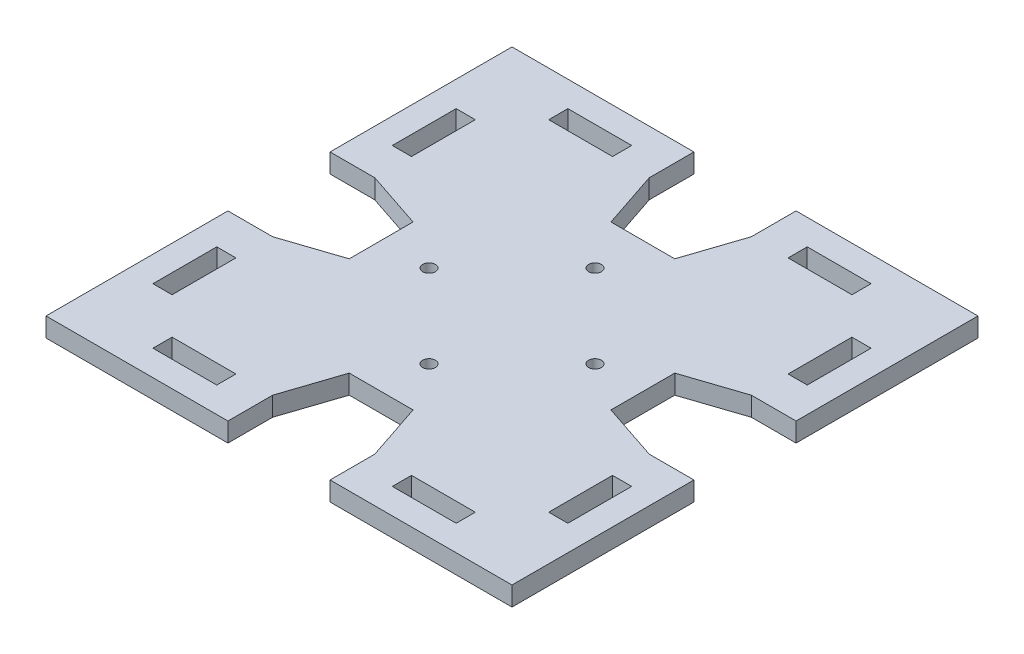
SolidWorks part; units mm, degrees
ref_plane "Front Plane" through (0, 0, 0) normal (0, 0, 1) x (1, 0, 0)
ref_plane "Top Plane" through (0, 0, 0) normal (0, 1, 0) x (1, 0, 0)
ref_plane "Right Plane" through (0, 0, 0) normal (1, 0, 0) x (0, 0, -1)
sketch "Sketch1" plane through (0, 0, 0) normal (0, 1, 0) x (1, 0, 0)
  line L5 (-31.5, 9) -> (-41.5, 9)
  line L6 (-41.5, 9) -> (-44.5, 0)
  line L7 (-31.5, 9) -> (-28.5, 0)
  line L8 (-57, 29.5) -> (-50.5, 29.5)
  line L9 (-31.5, 50) -> (-28.5, 59)
  line L10 (-31.5, 50) -> (-41.5, 50)
  line L11 (-41.5, 50) -> (-44.5, 59)
  line L15 (-16, 24.5) -> (-16, 34.5)
  line L16 (-16, 34.5) -> (-7, 37.5)
  line L17 (-16, 24.5) -> (-7, 21.5)
  line L19 (-36.5, 50) -> (-36.5, 43.5)
  line L20 (-57, 24.5) -> (-66, 21.5)
  line L21 (-57, 24.5) -> (-57, 34.5)
  line L22 (-57, 34.5) -> (-66, 37.5)
  line L24 (-7, 43.25) -> (-7, 53.25)
  line L27 (-7, 37.5) -> (0, 37.5)
  line L29 (-7, 53.25) -> (-4, 53.25)
  line L30 (-4, 53.25) -> (-4, 43.25)
  line L31 (-4, 43.25) -> (-7, 43.25)
  line L33 (-4, 15.75) -> (-7, 15.75)
  line L34 (-7, 5.75) -> (-4, 5.75)
  line L35 (-7, 15.75) -> (-7, 5.75)
  line L36 (-4, 5.75) -> (-4, 15.75)
  line L39 (-7, 21.5) -> (0, 21.5)
  line L40 (-69, 15.75) -> (-66, 15.75)
  line L41 (-66, 15.75) -> (-66, 5.75)
  line L42 (-66, 5.75) -> (-69, 5.75)
  line L43 (-69, 5.75) -> (-69, 15.75)
  line L46 (-66, 21.5) -> (-73, 21.5)
  line L47 (-66, 37.5) -> (-73, 37.5)
  line L48 (-69, 43.25) -> (-66, 43.25)
  line L49 (-66, 53.25) -> (-69, 53.25)
  line L50 (-66, 43.25) -> (-66, 53.25)
  line L51 (-69, 53.25) -> (-69, 43.25)
  line L56 (-73, 66) -> (-44.5, 66)
  line L58 (-44.5, 59) -> (-44.5, 66)
  line L59 (-28.5, 59) -> (-28.5, 66)
  line L60 (-28.5, 66) -> (0, 66)
  line L61 (0, 66) -> (0, 37.5)
  line L62 (-73, 66) -> (-73, 37.5)
  line L64 (-73, -7) -> (-44.5, -7)
  line L66 (-28.5, 0) -> (-28.5, -7)
  line L67 (-44.5, 0) -> (-44.5, -7)
  line L68 (-28.5, -7) -> (0, -7)
  line L69 (0, 21.5) -> (0, -7)
  line L70 (-73, 21.5) -> (-73, -7)
  line L71 (-50.25, -3) -> (-50.25, 0)
  line L72 (-22.75, 0) -> (-12.75, 0)
  line L73 (-12.75, 0) -> (-12.75, -3)
  line L74 (-12.75, -3) -> (-22.75, -3)
  line L75 (-22.75, -3) -> (-22.75, 0)
  line L76 (-50.25, 0) -> (-60.25, 0)
  line L77 (-60.25, 0) -> (-60.25, -3)
  line L78 (-60.25, -3) -> (-50.25, -3)
  line L79 (-12.75, 59) -> (-12.75, 62)
  line L80 (-12.75, 62) -> (-22.75, 62)
  line L81 (-22.75, 62) -> (-22.75, 59)
  line L82 (-22.75, 59) -> (-12.75, 59)
  line L83 (-50.25, 62) -> (-50.25, 59)
  line L84 (-60.25, 62) -> (-50.25, 62)
  line L85 (-60.25, 59) -> (-60.25, 62)
  line L86 (-50.25, 59) -> (-60.25, 59)
  line L87 (-36.5, 41.5) -> (-36.5, 17.5)
  line L88 (-48.5, 29.5) -> (-24.5, 29.5)
  line L89 (-22.5, 29.5) -> (-16, 29.5)
  line L90 (-36.5, 15.5) -> (-36.5, 12)
  circle A0 centre (-36.5, 42.5) radius 1
  circle A1 centre (-23.5, 29.5) radius 1
  circle A2 centre (-36.5, 16.5) radius 1
  circle A3 centre (-49.5, 29.5) radius 1
  point P7 (-44.5, 0)
  point P72 (0, 0)
  point P79 (0, 0)
  point P84 (0, 0)
  point P85 (0, 0)
  point P86 (0, 0)
  point P87 (0, 0)
  point P88 (-48.5, 29.5)
  point P89 (-48.5, 29.5)
  point P90 (0, 0)
  point P91 (0, 0)
  point P92 (0, 0)
  point P93 (-36.5, 29.5)
  dimension "D16" = 26
  dimension "D18" = 2
  dimension "D1" = 10
  dimension "D2" = 28.5
  dimension "D3" = 10
  dimension "D4" = 3
  dimension "D5" = 3
  dimension "D6" = 9
  dimension "D7" = 28.5
  dimension "D8" = 9
  dimension "D9" = 7
  dimension "D10" = 3
  dimension "D11" = 5.75
  dimension "D12" = 10
  dimension "D13" = 7
  dimension "D14" = 4
  dimension "D15" = 7
  dimension "D17" = 5.75
  dimension "D19" = 4
extrude "Boss-Extrude1" add sketch "Sketch1" along normal blind 3 contours L56 L62 L47 L22 L21 L8 L19 L10 L11 L58 L51 L49 L50 L48 L83 L86 L85 L84 | L46 L70 L64 L67 L6 L5 L19 L8 L21 L20 L78 L77 L76 L71 L42 L43 L40 L41 | L69 L39 L17 L15 L8 L19 L5 L7 L66 L68 L36 L34 L35 L33 L74 L75 L72 L73 | L61 L60 L59 L9 L10 L19 L8 L15 L16 L27 L82 L81 L80 L79 L30 L31 L24 L29
